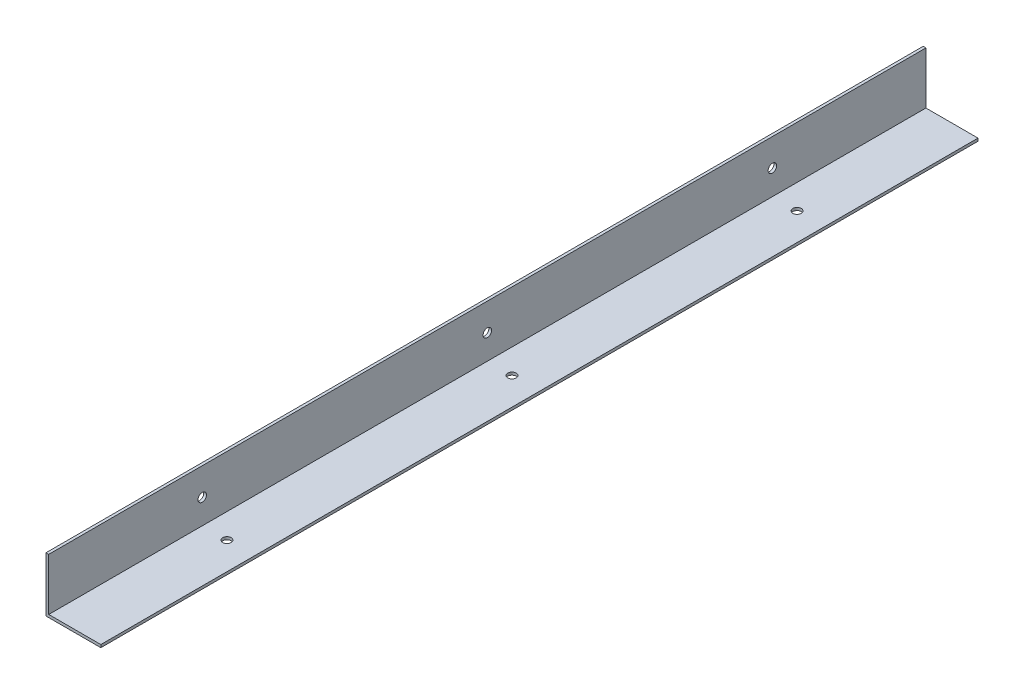
SolidWorks part; units mm, degrees
material "1060 Alloy"
ref_plane "Front Plane" through (0, 0, 0) normal (0, 0, 1) x (1, 0, 0)
ref_plane "Top Plane" through (0, 0, 0) normal (0, 1, 0) x (1, 0, 0)
ref_plane "Right Plane" through (0, 0, 0) normal (1, 0, 0) x (0, 0, -1)
sketch "Sketch2" plane through (0, 0, 0) normal (0, 0, 1) x (1, 0, 0)
  line L0 (0, 0) -> (0, 31.75)
  line L1 (0, 31.75) -> (1.5875, 31.75)
  line L2 (1.5875, 31.75) -> (1.5875, 1.5875)
  line L3 (1.5875, 1.5875) -> (31.75, 1.5875)
  line L4 (31.75, 1.5875) -> (31.75, 0)
  line L5 (31.75, 0) -> (0, 0)
  dimension "D1" = 31.75
  dimension "D2" = 1.5875
  dimension "D3" = 30.1625
  dimension "D4" = 31.75
extrude "Boss-Extrude1" add sketch "Sketch2" along normal blind 508
hole_wizard "#10 (0.1935) Diameter Hole2" positions "Sketch3" profile "Sketch4" hole size "#10" standard "ANSI Inch" end condition through all
sketch "Sketch3" plane through (0, 0, 0) normal (-1, 0, 0) x (0, 0, 1)
  line L0 (254, 31.75) -> (254, 0) construction
  line L1 (508, 31.75) -> (0, 31.75) construction
  line L2 (508, 0) -> (0, 0) construction
  line L4 (0, 15.875) -> (508, 15.875) construction
  line L5 (0, 31.75) -> (0, 0) construction
  line L6 (508, 31.75) -> (508, 0) construction
  point P17 (88.9, 15.875)
  point P19 (254, 15.875)
  point P21 (419.1, 15.875)
  dimension "D1" = 165.1
  dimension "D2" = 165.1
sketch "Sketch4" plane through (0, 15.875, 419.1) normal (0, 1, 0) x (0, 0, 1)
  line L0 (0, 0) -> (0, 31.75)
  line L1 (0, 31.75) -> (2.4574, 31.75)
  line L2 (2.4574, 31.75) -> (2.4574, 0)
  line L5 (2.4574, 0) -> (0, 0)
  line L11 (0, -6.35) -> (0, 107.95) construction
  dimension "Thru Hole Dia." = 4.9149
  dimension "Thru Hole Depth" = 31.75
hole_wizard "#10 (0.1935) Diameter Hole4" positions "Sketch5" profile "Sketch6" hole size "#10" standard "ANSI Inch" end condition through all
sketch "Sketch5" plane through (0, 0, 0) normal (0, -1, 0) x (-1, 0, 0)
  line L0 (0, -254) -> (-31.75, -254) construction
  line L1 (0, -508) -> (0, 0) construction
  line L2 (-31.75, -508) -> (-31.75, 0) construction
  line L4 (-15.875, 0) -> (-15.875, -508) construction
  line L5 (0, 0) -> (-31.75, 0) construction
  line L6 (0, -508) -> (-31.75, -508) construction
  point P15 (-15.875, -254)
  point P17 (-15.875, -88.9)
  point P19 (-15.875, -419.1)
  dimension "D1" = 165.1
  dimension "D2" = 165.1
sketch "Sketch6" plane through (15.875, 0, 419.1) normal (1, 0, 0) x (0, 0, -1)
  line L0 (0, 0) -> (0, 31.75)
  line L1 (0, 31.75) -> (2.4574, 31.75)
  line L2 (2.4574, 31.75) -> (2.4574, 0)
  line L5 (2.4574, 0) -> (0, 0)
  line L11 (0, -6.35) -> (0, 107.95) construction
  dimension "Thru Hole Dia." = 4.9149
  dimension "Thru Hole Depth" = 31.75
